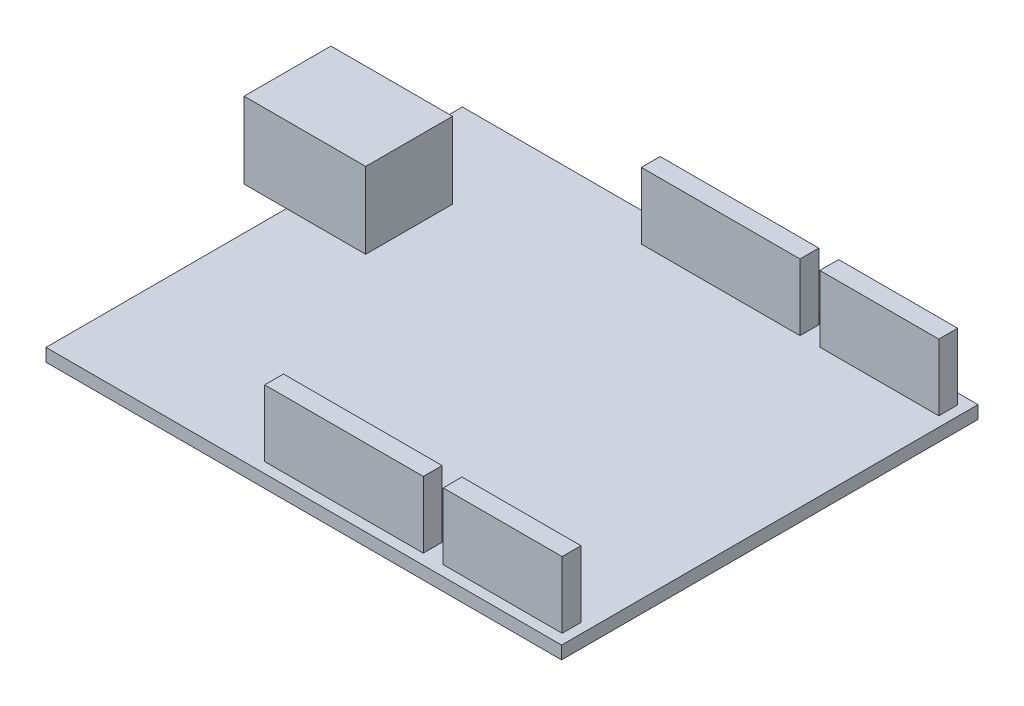
SolidWorks part; units mm, degrees
ref_plane "Front Plane" through (0, 0, 0) normal (0, 0, 1) x (1, 0, 0)
ref_plane "Top Plane" through (0, 0, 0) normal (0, 1, 0) x (1, 0, 0)
ref_plane "Right Plane" through (0, 0, 0) normal (1, 0, 0) x (0, 0, -1)
sketch "Sketch2" plane through (0, 0, 0) normal (0, 1, 0) x (1, 0, 0)
  line L1 (-33.02, 26.67) -> (33.02, 26.67)
  line L2 (-33.02, 26.67) -> (-33.02, -26.67)
  line L3 (-33.02, -26.67) -> (33.02, -26.67)
  line L4 (33.02, 26.67) -> (33.02, -26.67)
  line L5 (-33.02, 26.67) -> (33.02, -26.67) construction
  line L6 (-33.02, -26.67) -> (33.02, 26.67) construction
  point P0 (0, 0)
  dimension "D1" = 53.34
  dimension "D2" = 66.04
extrude "Boss-Extrude1" add sketch "Sketch2" along normal blind 1.65
sketch "Sketch3" plane through (0, 1.65, 0) normal (0, 1, 0) x (1, 0, 0)
  line L0 (-33.02, 26.67) -> (-33.02, -26.67) construction
  line L1 (-38.45, 15.2514) -> (-22.87, 15.2514)
  line L2 (-38.45, 15.2514) -> (-38.45, 4.1314)
  line L3 (-38.45, 4.1314) -> (-22.87, 4.1314)
  line L4 (-22.87, 15.2514) -> (-22.87, 4.1314)
  line L5 (-38.45, 15.2514) -> (-22.87, 4.1314) construction
  line L6 (-38.45, 4.1314) -> (-22.87, 15.2514) construction
  point P0 (-30.66, 9.6914)
  dimension "D1" = 11.12
  dimension "D2" = 15.58
  dimension "D3" = 10.15
extrude "Boss-Extrude2" add sketch "Sketch3" along normal blind 9.75
sketch "Sketch4" plane through (-38.45, 0, 0) normal (-1, 0, 0) x (0, 0, 1)
  line L0 (-15.2514, 1.65) -> (-4.1314, 1.65) construction
  line L2 (-12.2614, 7.5721) -> (-7.1014, 7.5721)
  line L3 (-4.1314, 11.4) -> (-4.1314, 1.65) construction
  line L4 (-12.2614, 7.5721) -> (-12.2614, 4.8321)
  line L5 (-13.8314, 9.8041) -> (-5.5314, 9.8041)
  line L6 (-13.8314, 9.8041) -> (-13.8314, 2.6)
  line L7 (-13.8314, 2.6) -> (-5.5314, 2.6)
  line L8 (-5.5314, 9.8041) -> (-5.5314, 2.6)
  line L9 (-13.8314, 9.8041) -> (-5.5314, 2.6) construction
  line L10 (-13.8314, 2.6) -> (-5.5314, 9.8041) construction
  line L15 (-12.2614, 4.8321) -> (-7.1014, 4.8321)
  line L16 (-7.1014, 7.5721) -> (-7.1014, 4.8321)
  line L17 (-12.2614, 7.5721) -> (-7.1014, 4.8321) construction
  line L18 (-12.2614, 4.8321) -> (-7.1014, 7.5721) construction
  point P8 (-9.6814, 6.2021)
  point P13 (-9.6814, 6.2021)
  point P14 (-9.6814, 6.2021)
  dimension "D1" = 0.95
  dimension "D2" = 7.2041
  dimension "D3" = 5.16
  dimension "D4" = 1.4
  dimension "D5" = 8.3
  dimension "D6" = 2.74
extrude "Cut-Extrude1" cut sketch "Sketch4" against normal blind 9.75
sketch "Sketch5" plane through (0, 1.65, 0) normal (0, 1, 0) x (1, 0, 0)
  line L0 (33.02, -26.67) -> (33.02, 26.67) construction
  line L1 (16.51, -25.33) -> (31.75, -25.33)
  line L2 (16.51, -25.33) -> (16.51, -22.92)
  line L3 (16.51, -22.92) -> (31.75, -22.92)
  line L4 (31.75, -25.33) -> (31.75, -22.92)
  line L5 (-33.02, -26.67) -> (33.02, -26.67) construction
  line L6 (-33.02, 0) -> (33.02, 0) construction
  line L7 (-6.35, -25.33) -> (13.97, -25.33)
  line L8 (-6.35, -25.33) -> (-6.35, -22.92)
  line L9 (-6.35, -22.92) -> (13.97, -22.92)
  line L10 (13.97, -25.33) -> (13.97, -22.92)
  line L11 (-33.02, 4.1314) -> (-33.02, -26.67) construction
  line L12 (16.51, 22.92) -> (31.75, 22.92)
  line L13 (31.75, 25.33) -> (31.75, 22.92)
  line L14 (16.51, 25.33) -> (31.75, 25.33)
  line L15 (16.51, 25.33) -> (16.51, 22.92)
  line L16 (-6.35, 22.92) -> (13.97, 22.92)
  line L17 (13.97, 25.33) -> (13.97, 22.92)
  line L18 (-6.35, 25.33) -> (13.97, 25.33)
  line L19 (-6.35, 25.33) -> (-6.35, 22.92)
  dimension "D1" = 15.24
  dimension "D2" = 2.41
  dimension "D3" = 1.27
  dimension "D4" = 1.34
  dimension "D5" = 20.32
  dimension "D6" = 2.54
extrude "Boss-Extrude3" add sketch "Sketch5" along normal blind 8.51
